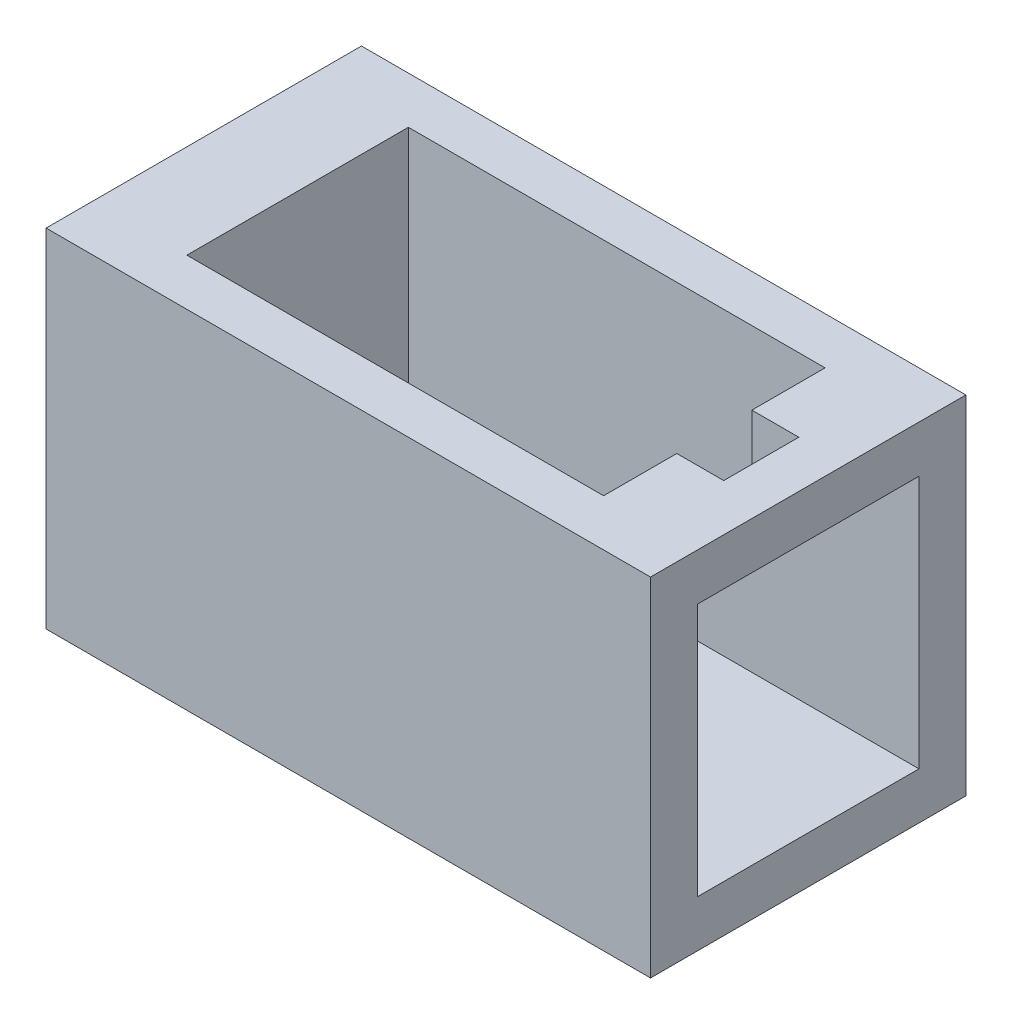
SolidWorks part; units mm, degrees
ref_plane "Front Plane" through (0, 0, 0) normal (0, 0, 1) x (1, 0, 0)
ref_plane "Top Plane" through (0, 0, 0) normal (0, 1, 0) x (1, 0, 0)
ref_plane "Right Plane" through (0, 0, 0) normal (1, 0, 0) x (0, 0, -1)
sketch "Sketch2" plane through (0, 0, 0) normal (0, 1, 0) x (1, 0, 0)
  line L1 (16.1, -8.4) -> (-16.1, -8.4)
  line L2 (16.1, -8.4) -> (16.1, 8.4)
  line L3 (16.1, 8.4) -> (-16.1, 8.4)
  line L4 (-16.1, -8.4) -> (-16.1, 8.4)
  line L5 (16.1, -8.4) -> (-16.1, 8.4) construction
  line L6 (16.1, 8.4) -> (-16.1, -8.4) construction
  point P0 (0, 0)
  dimension "D1" = 16.8
  dimension "D2" = 32.2
extrude "Boss-Extrude1" add sketch "Sketch2" against normal blind 18.5 contours L1 L4 L3 L2
sketch "Sketch3" plane through (0, 0, 0) normal (0, 1, 0) x (1, 0, 0)
  line L1 (11.1, -5.9) -> (-11.1, -5.9)
  line L2 (11.1, -5.9) -> (11.1, 5.9)
  line L3 (11.1, 5.9) -> (-11.1, 5.9)
  line L4 (-11.1, -5.9) -> (-11.1, 5.9)
  line L5 (11.1, -5.9) -> (-11.1, 5.9) construction
  line L6 (11.1, 5.9) -> (-11.1, -5.9) construction
  point P0 (0, 0)
  dimension "D1" = 11.8
  dimension "D2" = 22.2
extrude "Cut-Extrude1" cut sketch "Sketch3" against normal blind 16 contours L3 L4 L1 L2
sketch "Sketch4" plane through (16.1, 0, 0) normal (1, 0, 0) x (0, 0, -1)
  line L0 (0, 0) -> (0, -18.5) construction
  line L1 (-8.4, -18.5) -> (8.4, -18.5) construction
  line L3 (5.9, -16) -> (-5.9, -16)
  line L4 (5.9, -16) -> (5.9, -2.5)
  line L5 (5.9, -2.5) -> (-5.9, -2.5)
  line L6 (-5.9, -16) -> (-5.9, -2.5)
  point P5 (0, -9.25)
  dimension "D1" = 5.9
  dimension "D2" = 6.75
  dimension "D3" = 6.75
  dimension "D4" = 11.8
extrude "Cut-Extrude2" cut sketch "Sketch4" against normal blind 5
sketch "Sketch5" plane through (0, 0, 0) normal (0, 1, 0) x (1, 0, 0)
  line L0 (11.1, -5.9) -> (11.1, 5.9) construction
  line L1 (13.6, -2) -> (11.1, -2)
  line L2 (13.6, -2) -> (13.6, 2)
  line L3 (13.6, 2) -> (11.1, 2)
  line L7 (11.1, 2) -> (11.1, -2)
  point P0 (11.1, 0)
  dimension "D1" = 4
  dimension "D2" = 2
  dimension "D3" = 2.5
  dimension "D4" = 2.5
extrude "Cut-Extrude3" cut sketch "Sketch5" against normal blind 2.5
